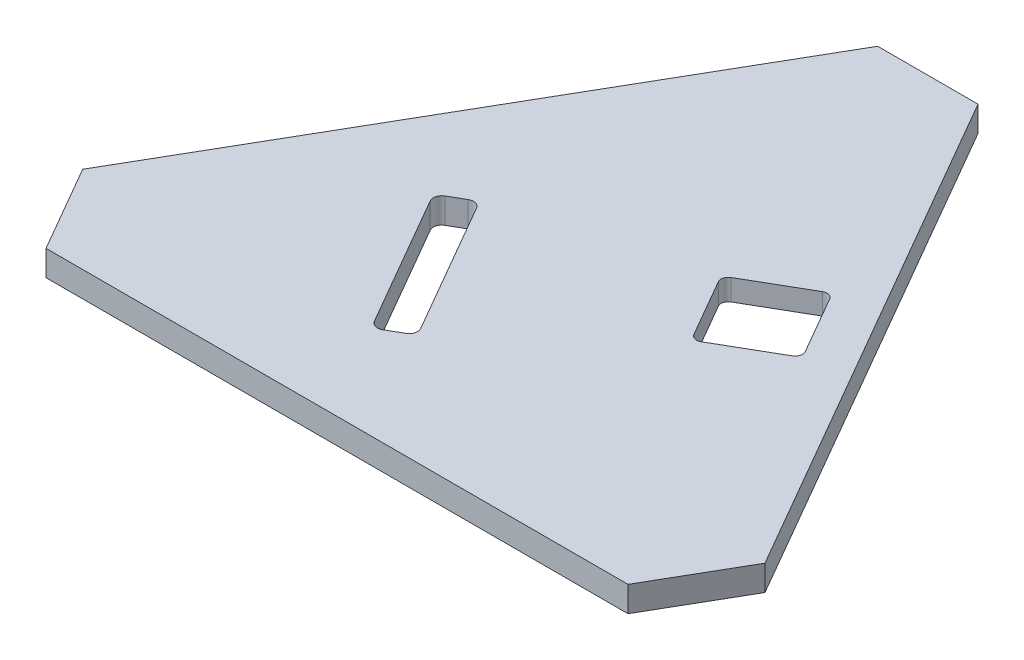
SolidWorks part; units mm, degrees
material "Beech"
ref_plane "Front Plane" through (0, 0, 0) normal (0, 0, 1) x (1, 0, 0)
ref_plane "Top Plane" through (0, 0, 0) normal (0, 1, 0) x (1, 0, 0)
ref_plane "Right Plane" through (0, 0, 0) normal (1, 0, 0) x (0, 0, -1)
sketch "Sketch1" plane through (-388.2817, 0, -288.1857) normal (0, 1, 0) x (1, 0, 0)
  line L0 (1747.5708, -13084.8246) -> (1672.5144, -13084.8246)
  line L1 (1672.5144, -13084.8246) -> (1454.7035, -13462.0841)
  line L2 (1454.7035, -13462.0841) -> (1492.2317, -13527.0849)
  line L3 (1492.2317, -13527.0849) -> (1927.8535, -13527.0849)
  line L4 (1927.8535, -13527.0849) -> (1965.3817, -13462.0841)
  line L5 (1965.3817, -13462.0841) -> (1747.5708, -13084.8246)
  line L9 (1681.81, -13068.724) -> (1641.3158, -13138.8621) construction
  line L11 (1548.8311, -13527.0849) -> (1464.0303, -13527.0849) construction
  line L14 (1978.4206, -13484.668) -> (1947.1007, -13430.4205) construction
  line L64 (1710.0426, -13357.9978) -> (1856.4763, -13273.4543) construction
  line L65 (1710.0426, -13357.9978) -> (1710.0426, -13527.0849) construction
  line L66 (1710.0426, -13357.9978) -> (1563.6089, -13273.4543) construction
extrude "Boss-Extrude1" add sketch "Sketch1" along normal blind 19.05
sketch "Sketch4" plane through (0, 19.05, 0) normal (0, 1, 0) x (1, 0, 0)
  line L2 (1438.2875, -12973.668) -> (1463.2875, -13016.9692)
  line L3 (1438.2875, -12973.668) -> (1463.2875, -13016.9692)
  line L16 (1565.553, -13173.8984) -> (1353.5156, -12806.6389)
  line L17 (1353.5156, -12806.6389) -> (1290.0061, -12806.6389)
  line L18 (1290.0061, -12806.6389) -> (1077.9688, -13173.8984)
  line L19 (1077.9688, -13173.8984) -> (1109.7235, -13228.8992)
  line L20 (1109.7235, -13228.8992) -> (1533.7982, -13228.8992)
  line L21 (1533.7982, -13228.8992) -> (1565.553, -13173.8984)
  line L22 (1565.553, -13173.8984) -> (1353.5156, -12806.6389)
  line L23 (1353.5156, -12806.6389) -> (1290.0061, -12806.6389)
  line L24 (1290.0061, -12806.6389) -> (1077.9688, -13173.8984)
  line L25 (1077.9688, -13173.8984) -> (1109.7235, -13228.8992)
  line L26 (1109.7235, -13228.8992) -> (1533.7982, -13228.8992)
  line L27 (1533.7982, -13228.8992) -> (1565.553, -13173.8984)
  line L40 (1455.0602, -13021.7192) -> (1430.0602, -12978.418)
  line L41 (1422.5471, -12976.4048) -> (1379.2458, -13001.4048)
  line L42 (1377.2327, -13008.918) -> (1402.2327, -13052.2192)
  line L43 (1409.7458, -13054.2324) -> (1453.0471, -13029.2324)
  line L44 (1455.0602, -13021.7192) -> (1430.0602, -12978.418)
  line L45 (1422.5471, -12976.4048) -> (1379.2458, -13001.4048)
  line L46 (1377.2327, -13008.918) -> (1402.2327, -13052.2192)
  line L47 (1409.7458, -13054.2324) -> (1453.0471, -13029.2324)
  arc A22 (1430.0602, -12978.418) -> (1422.5471, -12976.4048) centre (1425.2971, -12981.168) ccw
  arc A23 (1453.0471, -13029.2324) -> (1455.0602, -13021.7192) centre (1450.2971, -13024.4692) ccw
  arc A24 (1379.2458, -13001.4048) -> (1377.2327, -13008.918) centre (1381.9958, -13006.168) ccw
  arc A25 (1402.2327, -13052.2192) -> (1409.7458, -13054.2324) centre (1406.9958, -13049.4692) ccw
  arc A26 (1430.0602, -12978.418) -> (1422.5471, -12976.4048) centre (1425.2971, -12981.168) ccw
  arc A27 (1453.0471, -13029.2324) -> (1455.0602, -13021.7192) centre (1450.2971, -13024.4692) ccw
  arc A28 (1379.2458, -13001.4048) -> (1377.2327, -13008.918) centre (1381.9958, -13006.168) ccw
  arc A29 (1402.2327, -13052.2192) -> (1409.7458, -13054.2324) centre (1406.9958, -13049.4692) ccw
  dimension "D1" = 10
  dimension "D2" = 10
  dimension "D3" = 0.5
extrude "Cut-Extrude1" cut sketch "Sketch4" against normal blind 20 contours L46 A29 L47 A27 L44 A26 L45 A28
sketch "Sketch5" plane through (0, 0, 0) normal (0, -1, 0) x (1, 0, 0)
  line L0 (1422.5471, 12976.4048) -> (1379.2458, 13001.4048) construction
  line L1 (1427.6709, 12961.8996) -> (1364.122, 12998.5896)
  line L2 (1432.8755, 12963.2941) -> (1469.5655, 13026.8431)
  line L3 (1468.1709, 13032.0476) -> (1404.622, 13068.7376)
  line L4 (1362.7274, 13003.7941) -> (1399.4174, 13067.3431)
  line L5 (1430.9705, 12959.9946) -> (1401.3224, 13070.6426) construction
  line L6 (1471.4705, 13030.1426) -> (1360.8224, 13000.4946) construction
  circle A0 centre (1416.1464, 13015.3186) radius 27.5 construction
  arc A1 (1432.8755, 12963.2941) -> (1427.6709, 12961.8996) centre (1429.5759, 12965.1991) cw
  arc A2 (1364.122, 12998.5896) -> (1362.7274, 13003.7941) centre (1366.027, 13001.8891) cw
  arc A3 (1469.5655, 13026.8431) -> (1468.1709, 13032.0476) centre (1466.2659, 13028.7481) ccw
  arc A4 (1399.4174, 13067.3431) -> (1404.622, 13068.7376) centre (1402.717, 13065.4381) cw
  point P0 (1416.1464, 13015.3186)
  dimension "D2" = 3.81
  dimension "D1" = 10
extrude "Cut-Extrude2" cut sketch "Sketch5" against normal blind 3.175
sketch "Sketch6" plane through (0, 19.05, 0) normal (0, 1, 0) x (1, 0, 0)
  line L0 (1216.9644, -13064.3252) -> (1274.1144, -13163.3119)
  line L1 (1219.2887, -13055.651) -> (1230.2872, -13049.301)
  line L2 (1282.7887, -13165.6362) -> (1293.7872, -13159.2862)
  line L3 (1238.9615, -13051.6252) -> (1296.1115, -13150.6119)
  line L4 (1213.7894, -13058.826) -> (1299.2865, -13156.1112) construction
  line L5 (1277.2894, -13168.8112) -> (1235.7865, -13046.126) construction
  line L6 (1257.7835, -13033.426) -> (1321.2835, -13143.4112) construction
  line L7 (1323.7747, -12995.326) -> (1257.7835, -13033.426) construction
  line L8 (1321.2835, -13143.4112) -> (1387.2747, -13105.3112) construction
  arc A0 (1282.7887, -13165.6362) -> (1274.1144, -13163.3119) centre (1279.6137, -13160.1369) cw
  arc A1 (1296.1115, -13150.6119) -> (1293.7872, -13159.2862) centre (1290.6122, -13153.7869) cw
  arc A2 (1238.9615, -13051.6252) -> (1230.2872, -13049.301) centre (1233.4622, -13054.8002) ccw
  arc A3 (1216.9644, -13064.3252) -> (1219.2887, -13055.651) centre (1222.4637, -13061.1502) cw
  point P1 (1256.538, -13107.4686)
  dimension "D3" = 6.35
  dimension "D1" = 25.4
  dimension "D2" = 25.4
extrude "Cut-Extrude3" cut sketch "Sketch6" against normal up to surface (19.05 mm away) up to face at (1416.1464, 0, 13015.3186)
